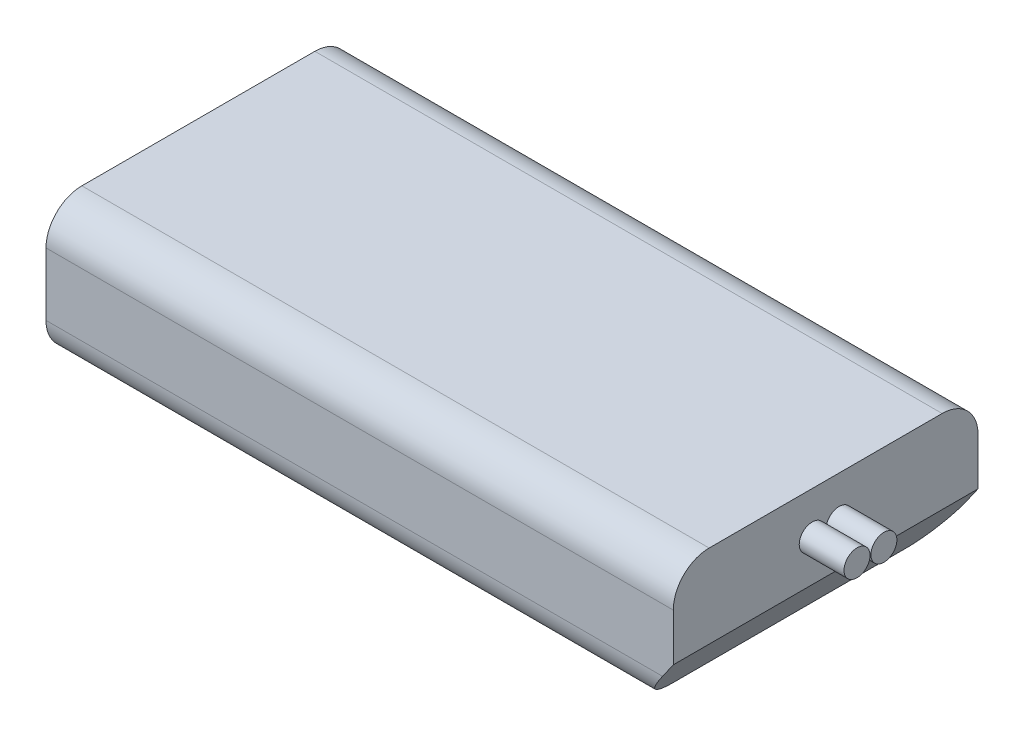
SolidWorks part; units mm, degrees
ref_plane "Front Plane" through (0, 0, 0) normal (0, 0, 1) x (1, 0, 0)
ref_plane "Top Plane" through (0, 0, 0) normal (0, 1, 0) x (1, 0, 0)
ref_plane "Right Plane" through (0, 0, 0) normal (1, 0, 0) x (0, 0, -1)
sketch "Sketch1" plane through (0, 0, 0) normal (0, 1, 0) x (1, 0, 0)
  line L1 (-17.5, -8.5) -> (17.5, -8.5)
  line L2 (-17.5, -8.5) -> (-17.5, 8.5)
  line L3 (-17.5, 8.5) -> (17.5, 8.5)
  line L4 (17.5, -8.5) -> (17.5, 8.5)
  line L5 (-17.5, -8.5) -> (17.5, 8.5) construction
  line L6 (-17.5, 8.5) -> (17.5, -8.5) construction
  point P0 (0, 0)
  dimension "D1" = 35
  dimension "D2" = 17
extrude "Boss-Extrude1" add sketch "Sketch1" along normal blind 7.5
chamfer "Chamfer1" distance 2 angle 55 1 edges at (17.5, 0, 0)
fillet "Fillet1" radius 2 4 edges at (-1, 0, -8.5) (-1, 0, 8.5) (0, 7.5, -8.5) (0, 7.5, 8.5)
sketch "Sketch3" plane through (17.5, 0, 0) normal (1, 0, 0) x (0, 0, -1)
  line L0 (6.5, 0) -> (-6.5, 0) construction
  circle A0 centre (-0.75, 5.158) radius 0.725
  circle A1 centre (0.75, 5.158) radius 0.725
  point P6 (0, 0)
  dimension "D1" = 1.45
  dimension "D2" = 1.45
  dimension "D3" = 1.5
  dimension "D4" = 0.75
extrude "Boss-Extrude2" add sketch "Sketch3" along normal blind 2.5
